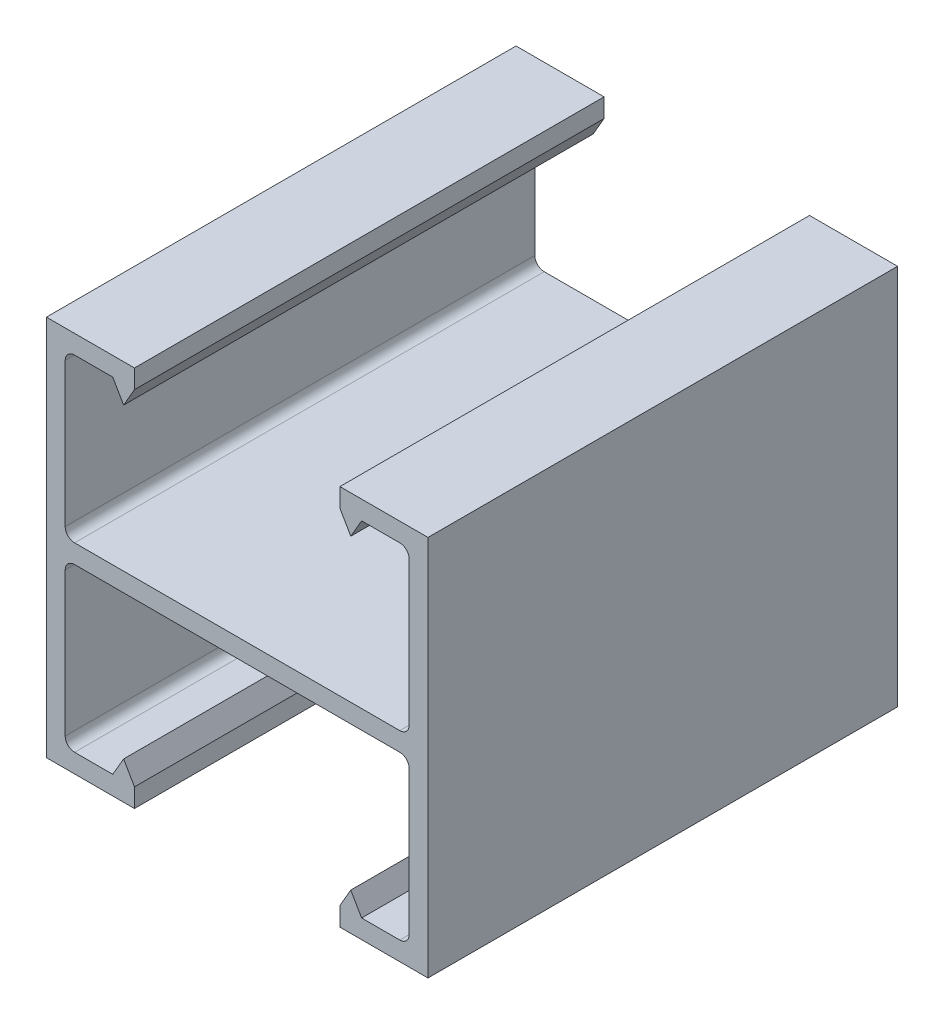
SolidWorks part; units mm, degrees
ref_plane "Plane1" through (0, 0, 0) normal (0, 0, 1) x (1, 0, 0)
ref_plane "Plane2" through (0, 0, 0) normal (0, 1, 0) x (1, 0, 0)
ref_plane "Plane3" through (0, 0, 0) normal (1, 0, 0) x (0, 0, -1)
sketch "Sketch1" plane through (0, 0, 0) normal (0, 0, 1) x (1, 0, 0)
  line L0 (-5.5563, 10.3188) -> (-10.3187, 10.3188)
  line L1 (-10.3187, 10.3188) -> (-10.3187, -10.3188)
  line L2 (-6.7294, -9.3028) -> (-8.7948, -9.3027)
  line L3 (10.3188, -10.3187) -> (10.3188, 10.3188)
  line L4 (10.3188, 10.3188) -> (5.5562, 10.3188)
  line L5 (8.7948, 9.3028) -> (6.7294, 9.3028)
  line L6 (9.3028, 1.016) -> (9.3028, 8.7948)
  line L7 (-8.7947, 0.508) -> (8.7948, 0.508)
  line L8 (-9.3027, 8.7948) -> (-9.3027, 1.016)
  line L9 (-6.7294, 9.3028) -> (-8.7948, 9.3027)
  line L10 (6.7294, 9.3028) -> (6.1428, 8.2868)
  line L11 (6.1428, 8.2868) -> (5.5562, 9.3028)
  line L12 (5.5562, 9.3028) -> (5.5562, 10.3188)
  line L13 (-6.7294, 9.3028) -> (-6.1428, 8.2868)
  line L14 (-6.1428, 8.2868) -> (-5.5563, 9.3028)
  line L15 (-5.5563, 9.3028) -> (-5.5563, 10.3188)
  line L16 (22.86, 0) -> (-25.4, 0) construction
  line L17 (6.1428, -8.2867) -> (5.5562, -9.3027)
  line L18 (6.7294, -9.3027) -> (6.1428, -8.2867)
  line L19 (8.7948, -9.3027) -> (6.7294, -9.3027)
  line L20 (10.3188, -10.3187) -> (5.5562, -10.3187)
  line L21 (5.5562, -9.3027) -> (5.5562, -10.3187)
  line L22 (-5.5562, -10.3188) -> (-10.3187, -10.3188)
  line L23 (-5.5562, -9.3028) -> (-5.5562, -10.3188)
  line L24 (-6.1428, -8.2868) -> (-5.5562, -9.3028)
  line L25 (-6.7294, -9.3028) -> (-6.1428, -8.2868)
  line L26 (-9.3027, -8.7948) -> (-9.3027, -1.016)
  line L27 (9.3028, -1.016) -> (9.3028, -8.7947)
  line L28 (-8.7947, -0.508) -> (8.7948, -0.508)
  arc A0 (-9.3027, 1.016) -> (-8.7947, 0.508) centre (-8.7947, 1.016) ccw
  arc A1 (-8.7948, 9.3027) -> (-9.3027, 8.7948) centre (-8.7948, 8.7948) ccw
  arc A2 (9.3028, 8.7948) -> (8.7948, 9.3028) centre (8.7948, 8.7948) ccw
  arc A3 (8.7948, 0.508) -> (9.3028, 1.016) centre (8.7948, 1.016) ccw
  arc A4 (9.3028, -8.7947) -> (8.7948, -9.3027) centre (8.7948, -8.7947) cw
  arc A5 (-8.7948, -9.3027) -> (-9.3027, -8.7948) centre (-8.7948, -8.7948) cw
  arc A6 (8.7948, -0.508) -> (9.3028, -1.016) centre (8.7948, -1.016) cw
  arc A7 (-9.3027, -1.016) -> (-8.7947, -0.508) centre (-8.7947, -1.016) cw
  dimension "D5" = 0.508
  dimension "Width" = 20.6375
  dimension "D8" = 10.3187
  dimension "D10" = 11.1125
  dimension "edge" = 4.7625
  dimension "D13" = 0.5866
  dimension "Height" = 20.6375
  dimension "D3" = 10.3187
  dimension "D4" = 60
extrude "Base-Extrude" add sketch "Sketch1" along normal mid plane 25.4
equation "\"D8@Sketch1\" = \"Width@Sketch1\" / 2"
equation "\"D10@Sketch1\" = \"Width@Sketch1\" - 2 * \"edge@Sketch1\""
equation "\"D5@Sketch1\" = \"gauge@Sketch1\" / 2"
equation "\"D3@Sketch1\" = \"Height@Sketch1\" / 2"
equation "\"D13@Sketch1\" = \"gauge@Sketch1\" * .577350269"
